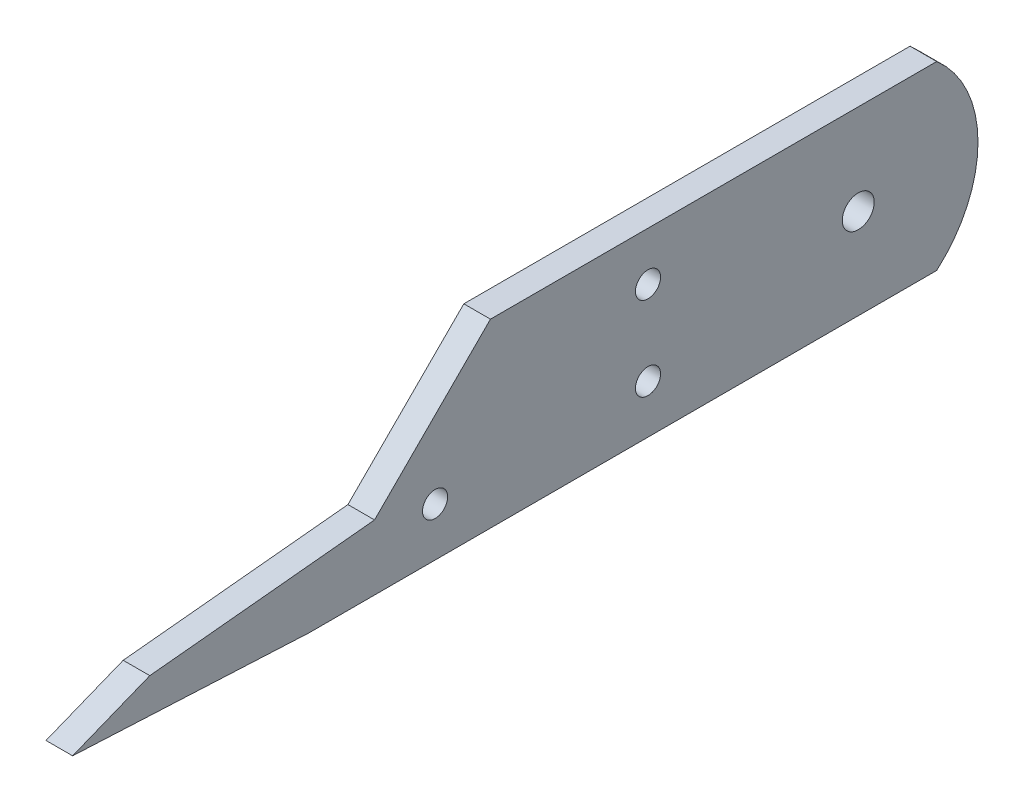
SolidWorks part; units mm, degrees
material "PE High Density"
ref_plane "Front Plane" through (0, 0, 0) normal (0, 0, 1) x (1, 0, 0)
ref_plane "Top Plane" through (0, 0, 0) normal (0, 1, 0) x (1, 0, 0)
ref_plane "Right Plane" through (0, 0, 0) normal (1, 0, 0) x (0, 0, -1)
sketch "Sketch1" plane through (0, 0, 0) normal (1, 0, 0) x (0, 0, -1)
  line L0 (-106.172, 0) -> (-62.992, 43.18)
  line L1 (0, 0) -> (-106.172, 0)
  line L2 (0, 0) -> (0, 2.54)
  line L3 (0, 43.18) -> (-62.992, 43.18)
  line L5 (0, 40.64) -> (-65.532, 40.64) construction
  line L6 (0, 2.54) -> (-103.632, 2.54) construction
  line L7 (0, 40.64) -> (0, 43.18)
  arc A0 (0, 40.64) -> (0, 2.54) centre (24.7621, 21.59) ccw
  dimension "D4" = 62.484
  dimension "D1" = 43.18
  dimension "D2" = 106.172
  dimension "D3" = 45
  dimension "D5" = 2.54
  dimension "D6" = 2.54
extrude "Boss-Extrude1" add sketch "Sketch1" along normal blind 6.35
sketch "Sketch2" plane through (6.35, 0, 0) normal (1, 0, 0) x (0, 0, -1)
  line L0 (-106.172, 0) -> (0, 0) construction
  line L1 (-68.072, 0) -> (-169.672, 0)
  line L2 (-169.672, 0) -> (-144.272, 10.16)
  line L3 (-144.272, 10.16) -> (-68.072, 17.78)
  line L4 (-68.072, 17.78) -> (-68.072, 0)
  dimension "D1" = 17.78
  dimension "D2" = 25.4
  dimension "D3" = 10.16
  dimension "D4" = 38.1
  dimension "D5" = 76.2
extrude "Boss-Extrude2" add sketch "Sketch2" against normal up to surface (6.35 mm away) up to face at (0, 21.59, 29.274)
sketch "Sketch3" plane through (6.35, 0, 0) normal (1, 0, 0) x (0, 0, -1)
  line L0 (-90.6498, 15.5222) -> (-106.172, 0) construction
  line L1 (-62.992, 43.18) -> (-90.6498, 15.5222) construction
  line L2 (-169.672, 0) -> (0, 0) construction
  line L3 (-106.172, 0) -> (-162.687, 2.794)
  line L4 (-144.272, 10.16) -> (-169.672, 0) construction
  line L5 (-162.687, 2.794) -> (-169.672, 0)
  line L6 (-169.672, 0) -> (-106.172, 0)
  dimension "D1" = 2.794
extrude "Cut-Extrude1" cut sketch "Sketch3" against normal through all
sketch "Sketch4" plane through (6.35, 0, 0) normal (1, 0, 0) x (0, 0, -1)
  line L1 (0, 0) -> (0, 2.54) construction
  line L2 (-25.4, 31.59) -> (-25.4, 11.59) construction
  circle A0 centre (-25.4, 31.59) radius 3
  circle A1 centre (-25.4, 11.59) radius 3
  arc A3 (0, 40.64) -> (0, 2.54) centre (24.7621, 21.59) ccw construction
  circle A4 centre (-76.2, 11.59) radius 3
  point P11 (-6.4799, 21.59)
  point P12 (-25.4, 21.59)
  dimension "D1" = 6
  dimension "D2" = 20
  dimension "D3" = 50.8
  dimension "D4" = 25.4
extrude "Cut-Extrude2" cut sketch "Sketch4" against normal through all
sketch "Sketch5" plane through (0, 0, 0) normal (-1, 0, 0) x (0, 0, 1)
  line L0 (0, 43.18) -> (-43.4811, 43.18)
  line L1 (0, 0) -> (-43.4811, 0)
  line L2 (0, 0) -> (0, 2.54) construction
  line L3 (0, 40.64) -> (0, 43.18) construction
  line L4 (0, 0) -> (0, 2.54)
  line L5 (0, 40.64) -> (0, 43.18)
  arc A0 (-43.4811, 43.18) -> (-43.4811, 0) centre (-24.7621, 21.59) ccw
  arc A2 (0, 2.54) -> (0, 40.64) centre (-24.7621, 21.59) ccw construction
  arc A3 (0, 2.54) -> (0, 40.64) centre (-24.7621, 21.59) ccw
  circle A4 centre (-24.7621, 21.59) radius 3.81
  dimension "D1" = 57.15
  dimension "D2" = 7.62
extrude "Boss-Extrude3" add sketch "Sketch5" against normal up to surface (6.35 mm away) up to face at (6.35, 31.59, 22.4)
